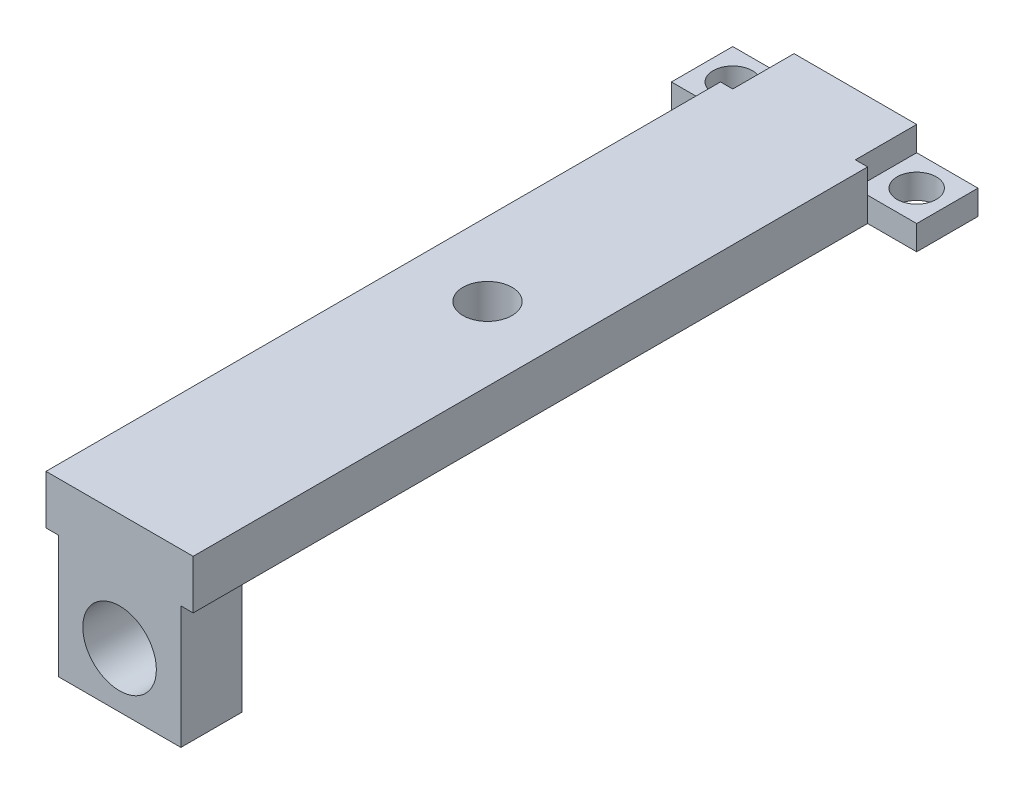
SolidWorks part; units mm, degrees
ref_plane "Front Plane" through (0, 0, 0) normal (0, 0, 1) x (1, 0, 0)
ref_plane "Top Plane" through (0, 0, 0) normal (0, 1, 0) x (1, 0, 0)
ref_plane "Right Plane" through (0, 0, 0) normal (1, 0, 0) x (0, 0, -1)
sketch "Sketch1" plane through (0, 0, 0) normal (0, 1, 0) x (1, 0, 0)
  line L1 (6, 30) -> (-6, 30)
  line L2 (6, 30) -> (6, -30)
  line L3 (6, -30) -> (-6, -30)
  line L4 (-6, 30) -> (-6, -30)
  line L5 (6, 30) -> (-6, -30) construction
  line L6 (6, -30) -> (-6, 30) construction
  point P0 (0, 0)
  dimension "D1" = 60
  dimension "D2" = 12
extrude "Boss-Extrude1" add sketch "Sketch1" along normal blind 4
sketch "Sketch2" plane through (0, 0, 0) normal (0, -1, 0) x (1, 0, 0)
  line L1 (-5, 30) -> (5, 30)
  line L2 (-5, 30) -> (-5, 25)
  line L3 (-5, 25) -> (5, 25)
  line L4 (5, 30) -> (5, 25)
  line L5 (-6, 30) -> (6, 30) construction
  point P7 (0, 30)
  point P8 (0, 30)
  dimension "D1" = 5
  dimension "D2" = 10
extrude "Boss-Extrude2" add sketch "Sketch2" along normal blind 10
sketch "Sketch3" plane through (0, 0, 30) normal (0, 0, 1) x (1, 0, 0)
  line L0 (5, -10) -> (-5, -10) construction
  line L1 (5, -10) -> (-5, -10) construction
  circle A0 centre (0, -5.5) radius 3
  point P7 (0, -10)
  dimension "D1" = 6
  dimension "D2" = 4.5
extrude "Cut-Extrude1" cut sketch "Sketch3" against normal up to next
sketch "Sketch4" plane through (0, 4, 0) normal (0, 1, 0) x (1, 0, 0)
  circle A0 centre (0, 0) radius 2
  dimension "D1" = 4
sketch "Sketch6" plane through (0, 0, 0) normal (0, 1, 0) x (1, 0, 0)
  line L0 (6, 30) -> (-6, 30) construction
  line L1 (10, 25) -> (-10, 25)
  line L2 (10, 25) -> (10, 30)
  line L3 (10, 30) -> (-10, 30)
  line L4 (-10, 25) -> (-10, 30)
  line L5 (-6, 30) -> (-6, -30) construction
  point P8 (0, 30)
  point P9 (0, 30)
  point P14 (-10, 27.5)
  dimension "D1" = 5
  dimension "D2" = 4
extrude "Boss-Extrude4" add sketch "Sketch6" along normal blind 2
sketch "Sketch13" plane through (0, 2, 0) normal (0, 1, 0) x (1, 0, 0)
  line L0 (-10, 30) -> (-10, 25) construction
  line L2 (-5, 30) -> (-10, 30)
  line L3 (-5, 30) -> (-5, 25)
  line L4 (-5, 25) -> (-10, 25)
  line L5 (-10, 30) -> (-10, 25)
  line L6 (-5, 30) -> (-10, 25) construction
  line L7 (-5, 25) -> (-10, 30) construction
  point P0 (-10, 29.4179)
  point P5 (-10, 27.5)
extrude "Cut-Extrude2" cut sketch "Sketch13" along normal up to next
sketch "Sketch14" plane through (0, 2, 0) normal (0, 1, 0) x (1, 0, 0)
  line L0 (-5, 25) -> (-5, 30) construction
  line L1 (-5, 30) -> (-10, 30) construction
  line L2 (-10, 30) -> (-10, 25) construction
  circle A0 centre (-7.5, 27.5) radius 1.6
  point P4 (-5, 27.5)
  point P5 (0, 0)
  point P8 (-7.5, 30)
  point P9 (0, 0)
  point P12 (-10, 27.5)
  dimension "D1" = 3.2
extrude "Cut-Extrude3" cut sketch "Sketch14" against normal up to next
mirror "Mirror1" about plane through (0, 0, 0) normal (1, 0, 0) of "Cut-Extrude2", "Cut-Extrude3"
extrude "Cut-Extrude4" cut sketch "Sketch4" against normal up to next
